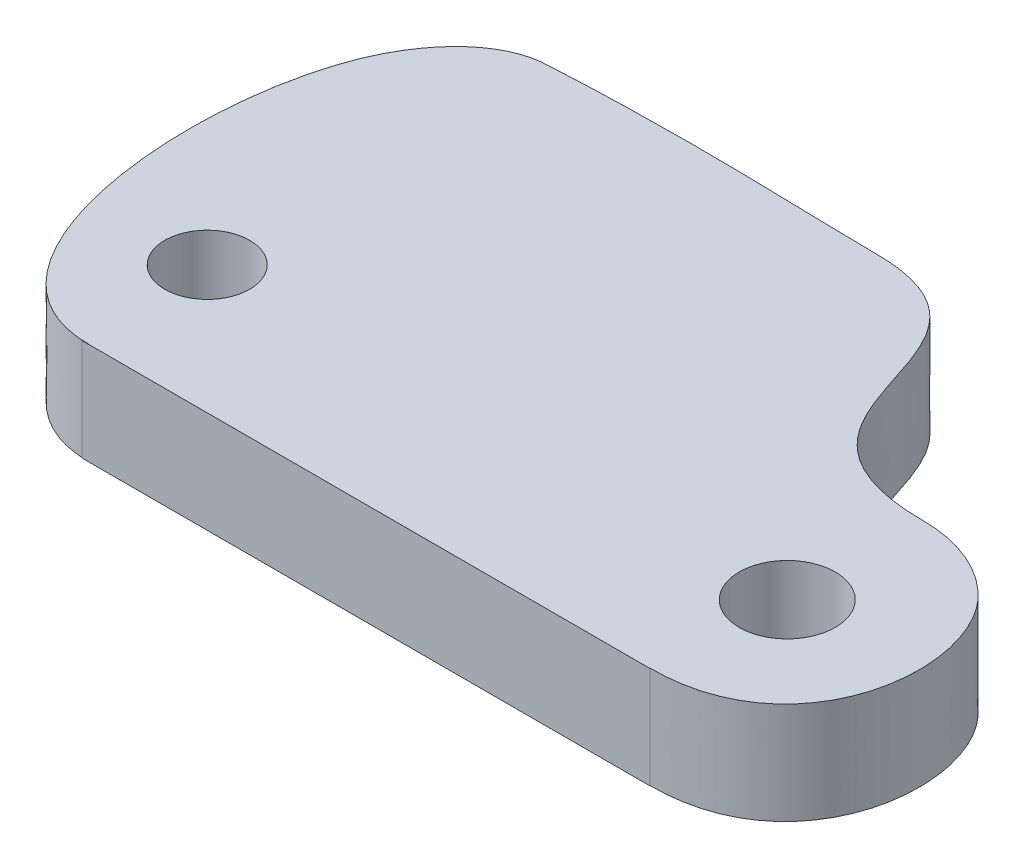
SolidWorks part; units mm, degrees
ref_plane "Front Plane" through (0, 0, 0) normal (0, 0, 1) x (1, 0, 0)
ref_plane "Top Plane" through (0, 0, 0) normal (0, 1, 0) x (1, 0, 0)
ref_plane "Right Plane" through (0, 0, 0) normal (1, 0, 0) x (0, 0, -1)
sketch "Sketch1" plane through (0, 0, 0) normal (0, 1, 0) x (1, 0, 0)
  line L1265 (24.2524, 153.0473) -> (24.0667, 153.0371)
  line L1266 (24.0667, 153.0371) -> (41.7809, 153.0371)
  line L1267 (41.7809, 153.0371) -> (41.7809, 153.0472)
  circle A0 centre (23.9667, 157.0371) radius 1.3251
  circle A1 centre (42.0665, 157.0371) radius 1.5002
  spline S1560 degree 3 poles (41.7809, 153.0472) (46.4725, 153.0236) (46.938, 158.3554) (44.8014, 160.2536) knots 0.3 0.3 0.3 0.3 0.4 0.4 0.4 0.4
  spline S1561 degree 3 poles (44.8014, 160.2536) (44.0761, 160.9184) (43.0923, 161.292) (42.0666, 161.292) knots 0.4 0.4 0.4 0.4 0.5 0.5 0.5 0.5
  spline S1562 degree 3 poles (42.0666, 161.292) (35.8728, 161.3054) (39.5756, 167.746) (34.1227, 167.769) knots 0.5 0.5 0.5 0.5 0.6 0.6 0.6 0.6
  spline S1563 degree 3 poles (34.1227, 167.769) (31.6575, 167.7794) (28.3617, 167.9935) (23.9667, 167.746) knots 0.6 0.6 0.6 0.6 0.7 0.7 0.7 0.7
  spline S1564 degree 3 poles (23.9667, 167.746) (22.941, 167.746) (21.9572, 167.0799) (21.2319, 165.8948) knots 0.7 0.7 0.7 0.7 0.8 0.8 0.8 0.8
  spline S1565 degree 3 poles (21.2319, 165.8948) (19.0953, 162.5108) (19.5608, 153.0054) (24.2524, 153.0473) knots 0.8 0.8 0.8 0.8 1 1 1 1
extrude "Boss-Extrude1" add sketch "Sketch1" along normal blind 3.175
